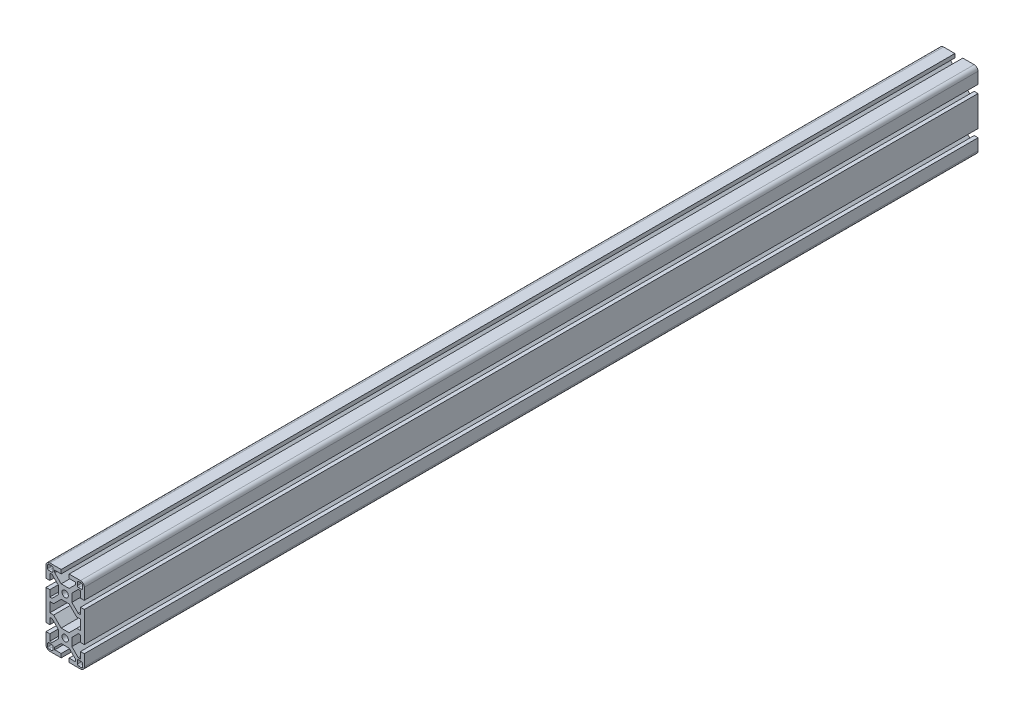
SolidWorks part; units mm, degrees
material "1060 Alloy"
ref_plane "Front" through (0, 0, 0) normal (0, 0, 1) x (1, 0, 0)
ref_plane "Top" through (0, 0, 0) normal (0, 1, 0) x (1, 0, 0)
ref_plane "Right" through (0, 0, 0) normal (1, 0, 0) x (0, 0, -1)
ref_plane "Plane1" through (0, 0, 25) normal (0, 0, 1) x (1, 0, 0)
sketch "Sketch1" plane through (0, 0, 25) normal (0, 0, 1) x (1, 0, 0)
  line L0 (-9.5, 12.7) -> (-9.5, 10.5)
  line L1 (-10.5, 9.5) -> (-12.7, 9.5)
  line L2 (-13.7, 10.5) -> (-13.7, 12.7)
  line L3 (-12.7, 13.7) -> (-10.5, 13.7)
  line L4 (12.7, 9.5) -> (10.5, 9.5)
  line L5 (9.5, 10.5) -> (9.5, 12.7)
  line L6 (10.5, 13.7) -> (12.7, 13.7)
  line L7 (13.7, 12.7) -> (13.7, 10.5)
  line L8 (-12.7, -39.5) -> (-10.5, -39.5)
  line L9 (-9.5, -40.5) -> (-9.5, -42.7)
  line L10 (-10.5, -43.7) -> (-12.7, -43.7)
  line L11 (-13.7, -42.7) -> (-13.7, -40.5)
  line L12 (9.5, -42.7) -> (9.5, -40.5)
  line L13 (10.5, -39.5) -> (12.7, -39.5)
  line L14 (13.7, -40.5) -> (13.7, -42.7)
  line L15 (12.7, -43.7) -> (10.5, -43.7)
  line L16 (0, 0) -> (-18.8009, 18.8009) construction
  line L17 (0, 0) -> (15.8468, 15.8468) construction
  line L18 (0, 0) -> (0, -54.7376) construction
  line L19 (0, -30) -> (18.7024, -48.7024) construction
  line L20 (0, -30) -> (-20.187, -50.187) construction
  line L21 (10.2713, -21.85) -> (12, -21.85)
  line L22 (12, -21.85) -> (12, -26.9)
  line L23 (3.1287, -24.75) -> (9.0287, -18.85)
  line L24 (-12, -18.85) -> (-9.0287, -18.85)
  line L26 (-11.3684, -30) -> (11.3684, -30) construction
  line L27 (9.0287, -18.85) -> (12, -18.85)
  line L33 (3.1287, -24.75) -> (-3.1287, -24.75)
  line L34 (-3.1287, -24.75) -> (-9.0287, -18.85)
  line L36 (-12, -18.85) -> (-12, -11.15)
  line L37 (-12, -11.15) -> (-9.0287, -11.15)
  line L38 (-9.0287, -11.15) -> (-3.1287, -5.25)
  line L39 (-3.1287, -5.25) -> (3.1287, -5.25)
  line L40 (3.1287, -5.25) -> (9.0287, -11.15)
  line L41 (9.0287, -11.15) -> (12, -11.15)
  line L42 (12, -11.15) -> (12, -18.85)
  line L44 (12, -26.9) -> (15, -26.9)
  line L47 (15, -26.9) -> (15, -3.1)
  line L50 (15, -3.1) -> (12, -3.1)
  line L51 (12, -3.1) -> (12, -8.15)
  line L52 (12, -8.15) -> (10.2713, -8.15)
  line L53 (10.2713, -8.15) -> (5.25, -3.1287)
  line L57 (5.25, -3.1287) -> (5.25, 3.1287)
  line L58 (5.25, 3.1287) -> (10.2713, 8.15)
  line L59 (10.2713, 8.15) -> (12, 8.15)
  line L60 (12, 8.15) -> (12, 3.1)
  line L61 (12, 3.1) -> (15, 3.1)
  line L64 (15, 3.1) -> (15, 12)
  line L65 (12, 15) -> (3.1, 15)
  line L68 (3.1, 15) -> (3.1, 12)
  line L69 (3.1, 12) -> (8.15, 12)
  line L70 (8.15, 12) -> (8.15, 10.2713)
  line L71 (8.15, 10.2713) -> (3.1287, 5.25)
  line L75 (3.1287, 5.25) -> (-3.1287, 5.25)
  line L76 (-3.1287, 5.25) -> (-8.15, 10.2713)
  line L77 (-8.15, 10.2713) -> (-8.15, 12)
  line L78 (-8.15, 12) -> (-3.1, 12)
  line L79 (-3.1, 12) -> (-3.1, 15)
  line L82 (-3.1, 15) -> (-12, 15)
  line L83 (-15, 12) -> (-15, 3.1)
  line L86 (-15, 3.1) -> (-12, 3.1)
  line L87 (-12, 3.1) -> (-12, 8.15)
  line L88 (-12, 8.15) -> (-10.2713, 8.15)
  line L89 (-10.2713, 8.15) -> (-5.25, 3.1287)
  line L93 (-5.25, 3.1287) -> (-5.25, -3.1287)
  line L94 (-5.25, -3.1287) -> (-10.2713, -8.15)
  line L95 (-10.2713, -8.15) -> (-12, -8.15)
  line L96 (-12, -8.15) -> (-12, -3.1)
  line L97 (-12, -3.1) -> (-15, -3.1)
  line L100 (-15, -3.1) -> (-15, -26.9)
  line L103 (-15, -26.9) -> (-12, -26.9)
  line L104 (-12, -26.9) -> (-12, -21.85)
  line L105 (-12, -21.85) -> (-10.2713, -21.85)
  line L106 (-10.2713, -21.85) -> (-5.25, -26.8713)
  line L110 (-5.25, -26.8713) -> (-5.25, -33.1287)
  line L111 (-5.25, -33.1287) -> (-10.2713, -38.15)
  line L112 (-10.2713, -38.15) -> (-12, -38.15)
  line L113 (-12, -38.15) -> (-12, -33.1)
  line L114 (-12, -33.1) -> (-15, -33.1)
  line L117 (-15, -33.1) -> (-15, -42)
  line L118 (-12, -45) -> (-3.1, -45)
  line L121 (-3.1, -45) -> (-3.1, -42)
  line L122 (-3.1, -42) -> (-8.15, -42)
  line L123 (-8.15, -42) -> (-8.15, -40.2713)
  line L124 (-8.15, -40.2713) -> (-3.1287, -35.25)
  line L125 (-3.1287, -35.25) -> (3.1287, -35.25)
  line L129 (3.1287, -35.25) -> (8.15, -40.2713)
  line L130 (8.15, -40.2713) -> (8.15, -42)
  line L131 (8.15, -42) -> (3.1, -42)
  line L132 (3.1, -42) -> (3.1, -45)
  line L135 (3.1, -45) -> (12, -45)
  line L136 (15, -42) -> (15, -33.1)
  line L139 (15, -33.1) -> (12, -33.1)
  line L140 (12, -33.1) -> (12, -38.15)
  line L141 (12, -38.15) -> (10.2713, -38.15)
  line L142 (10.2713, -38.15) -> (5.25, -33.1287)
  line L143 (5.25, -33.1287) -> (5.25, -26.8713)
  line L147 (5.25, -26.8713) -> (10.2713, -21.85)
  arc A0 (-9.5, 10.5) -> (-10.5, 9.5) centre (-10.5, 10.5) cw
  arc A1 (-12.7, 9.5) -> (-13.7, 10.5) centre (-12.7, 10.5) cw
  arc A2 (-13.7, 12.7) -> (-12.7, 13.7) centre (-12.7, 12.7) cw
  arc A3 (-10.5, 13.7) -> (-9.5, 12.7) centre (-10.5, 12.7) cw
  arc A4 (10.5, 9.5) -> (9.5, 10.5) centre (10.5, 10.5) cw
  arc A5 (9.5, 12.7) -> (10.5, 13.7) centre (10.5, 12.7) cw
  arc A6 (12.7, 13.7) -> (13.7, 12.7) centre (12.7, 12.7) cw
  arc A7 (13.7, 10.5) -> (12.7, 9.5) centre (12.7, 10.5) cw
  arc A8 (-10.5, -39.5) -> (-9.5, -40.5) centre (-10.5, -40.5) cw
  arc A9 (-9.5, -42.7) -> (-10.5, -43.7) centre (-10.5, -42.7) cw
  arc A10 (-12.7, -43.7) -> (-13.7, -42.7) centre (-12.7, -42.7) cw
  arc A11 (-13.7, -40.5) -> (-12.7, -39.5) centre (-12.7, -40.5) cw
  arc A12 (9.5, -40.5) -> (10.5, -39.5) centre (10.5, -40.5) cw
  arc A13 (12.7, -39.5) -> (13.7, -40.5) centre (12.7, -40.5) cw
  arc A14 (13.7, -42.7) -> (12.7, -43.7) centre (12.7, -42.7) cw
  arc A15 (10.5, -43.7) -> (9.5, -42.7) centre (10.5, -42.7) cw
  circle A16 centre (0, 0) radius 2.45
  circle A17 centre (0, -30) radius 2.45
  arc A63 (15, 12) -> (12, 15) centre (12, 12) ccw
  arc A79 (-12, 15) -> (-15, 12) centre (-12, 12) ccw
  arc A110 (-15, -42) -> (-12, -45) centre (-12, -42) ccw
  arc A126 (12, -45) -> (15, -42) centre (12, -42) ccw
  point P52 (5.25, 0)
  point P55 (-7.55, -45)
  point P59 (-12, -21.0324)
  point P61 (12, -18.5168)
  point P62 (-9.892, -18.078)
  point P63 (-11.9515, -21.0324)
  point P64 (-11.2586, -20.8627)
  point P65 (-10.9444, -21.1769)
  point P66 (-5.2831, -26.9)
  point P68 (-5.2522, -26.9)
  point P69 (-12, -11.15)
  point P70 (-11.8006, -11.15)
  point P72 (-8.5893, -11.15)
  point P73 (-9.1314, -11.2527)
  point P75 (-3.8713, -5.25)
  point P76 (-3.1287, -5.25)
  point P77 (3.1287, -5.25)
  point P78 (2.885, -5.25)
  point P79 (9.0287, -11.15)
  point P80 (9.0977, -11.15)
  point P81 (12, -11.15)
  point P82 (12, -11.2299)
  point P83 (-3.1, -24.75)
  point P84 (-2.9973, -24.7643)
  point P86 (12, -26.9)
  point P87 (12, -26.8713)
  point P90 (15, -26.9)
  point P91 (15, -26.8713)
  point P92 (4.7458, -27.4055)
  point P93 (4.7158, -27.497)
  point P96 (4.4927, -32.3432)
  point P97 (4.7171, -32.5958)
  point P98 (9.3995, -37.2853)
  point P99 (0, 0)
  point P100 (12, -37.2782)
  point P102 (11.9402, -37.2782)
  point P103 (12, -33.1)
  point P104 (12.0669, -33.1)
  point P105 (15, -33.1)
  point P108 (15, -33.1287)
  point P109 (-12, -38.15)
  point P111 (-11.9719, -38.15)
  point P112 (-12.0254, -38.15)
  point P113 (-10.5579, -38.15)
  point P114 (-10.2713, -38.15)
  point P116 (-10.3072, -38.15)
  point P117 (-5.25, -33.1287)
  point P118 (-5.25, -33.1)
  point P119 (-3.1, -35.25)
  point P122 (4.3342, -35.25)
  point P123 (3.1, -35.25)
  point P124 (-8.15, -40.2127)
  point P125 (-8.1207, -40.3542)
  point P126 (-8.15, -43.6)
  point P127 (0, 0)
  point P128 (-8.3615, -43.6)
  point P129 (-3.1, -45)
  point P131 (-3.1, -44.9123)
  point P132 (-3.1, -43.6167)
  point P133 (-3.1, -43.7)
  point P134 (3.1, -42)
  point P135 (0, 0)
  point P136 (3.1, -45)
  point P137 (3.1287, -45)
  point P138 (8.15, -40.2713)
  point P139 (8.15, -40.3037)
  point P140 (8.15, -42)
  point P143 (8.15, -41.9553)
  point P165 (-13.5, 3.1)
  point P166 (-10.5143, -11.15)
  dimension "D1" = 4.9
  dimension "D2" = 15
  dimension "D4" = 3
  dimension "D14" = 3
  dimension "D32" = 30
  dimension "D33" = 4.9
  dimension "D34" = 15
  dimension "D50" = 5.25
  dimension "D54" = 3
  dimension "D55" = 5.25
  dimension "D57" = 3
  dimension "D3" = 15
  dimension "D5" = 3.1
  dimension "D6" = 3
  dimension "D7" = 9.75
  dimension "D8" = 9.75
  dimension "D9" = 15
  dimension "D10" = 9.75
  dimension "D11" = 8.15
  dimension "D12" = 16.3
  dimension "D13" = 6.2
  dimension "D15" = 45
  dimension "D16" = 45
  dimension "D17" = 1.5
  dimension "D18" = 3
  dimension "D19" = 1.5
  dimension "D20" = 3
  dimension "D21" = 3
  dimension "D22" = 3
  dimension "D23" = 3.1
  dimension "D24" = 6.2
  dimension "D25" = 8.15
  dimension "D26" = 16.3
  dimension "D27" = 3
  dimension "D28" = 3
  dimension "D29" = 3
  dimension "D30" = 3
  dimension "D31" = 3
  dimension "D35" = 1.5
  dimension "D36" = 3.1
  dimension "D37" = 3.1
  dimension "D38" = 45
  dimension "D39" = 45
  dimension "D40" = 1.5
  dimension "D41" = 1.5
  dimension "D42" = 3
  dimension "D43" = 3
  dimension "D44" = 3
  dimension "D45" = 3
  dimension "D46" = 3
  dimension "D47" = 8.15
  dimension "D48" = 5.25
  dimension "D49" = 5.25
  dimension "D51" = 3
  dimension "D52" = 5.25
  dimension "D53" = 16.3
  dimension "D56" = 3
extrude "Boss-Extrude1" add sketch "Sketch1" against normal blind 700
sketch "Sketch2" plane through (15, 0, 0) normal (1, 0, 0) x (0, 0, -1)
  line L0 (-25, -30) -> (30, -30) construction
  line L1 (-25, -3.1287) -> (-25, 3.1287) construction
  line L3 (675, 15) -> (-25, 15) construction
  line L4 (-25, 3.1) -> (-25, 12) construction
  circle A0 centre (30, -30) radius 3
  point P4 (-25, -30)
  point P11 (0, 0)
  dimension "D2" = 6
  dimension "D1" = 45
  dimension "D3" = 55
extrude "Cut-Extrude1" cut sketch "Sketch2" against normal through all
hole_wizard "M6x1.0 Tapped Hole1" positions "Sketch3" profile "Sketch4" tap size "M6x1.0" standard "ANSI Metric"
sketch "Sketch3" plane through (0, 0, 25) normal (0, 0, 1) x (1, 0, 0)
  point P0 (0, 0)
  point P3 (0, -30)
sketch "Sketch4" plane through (0, 0, 25) normal (1, 0, 0) x (0, -1, 0)
  line L0 (0, 0) -> (0, 29.5022)
  line L1 (0, 29.5022) -> (2.5, 28)
  line L2 (2.5, 28) -> (2.5, 0)
  line L5 (2.5, 0) -> (0, 0)
  line L10 (0, 29.5022) -> (-2.5, 28) construction
  line L11 (0, -6.35) -> (0, 107.95) construction
  dimension "Tap Drill Dia." = 5
  dimension "Tap Drill Depth" = 28
  dimension "Drill Angle" = 118
cosmetic thread "Hole Thread1" parameters "D1"=25, "D2"=6
cosmetic thread "Hole Thread2" parameters "D1"=25, "D2"=6
hole_wizard "M6x1.0 Tapped Hole2" positions "Sketch5" profile "Sketch6" tap size "M6x1.0" standard "ANSI Metric"
sketch "Sketch5" plane through (0, 0, -675) normal (0, 0, -1) x (-1, 0, 0)
  point P0 (0, 0)
  point P3 (0, -30)
sketch "Sketch6" plane through (0, 0, -675) normal (1, 0, 0) x (0, 1, 0)
  line L0 (0, 0) -> (0, 29.5022)
  line L1 (0, 29.5022) -> (2.5, 28)
  line L2 (2.5, 28) -> (2.5, 0)
  line L5 (2.5, 0) -> (0, 0)
  line L10 (0, 29.5022) -> (-2.5, 28) construction
  line L11 (0, -6.35) -> (0, 107.95) construction
  dimension "Tap Drill Dia." = 5
  dimension "Tap Drill Depth" = 28
  dimension "Drill Angle" = 118
cosmetic thread "Hole Thread3" parameters "D1"=25, "D2"=6
cosmetic thread "Hole Thread4" parameters "D1"=25, "D2"=6
